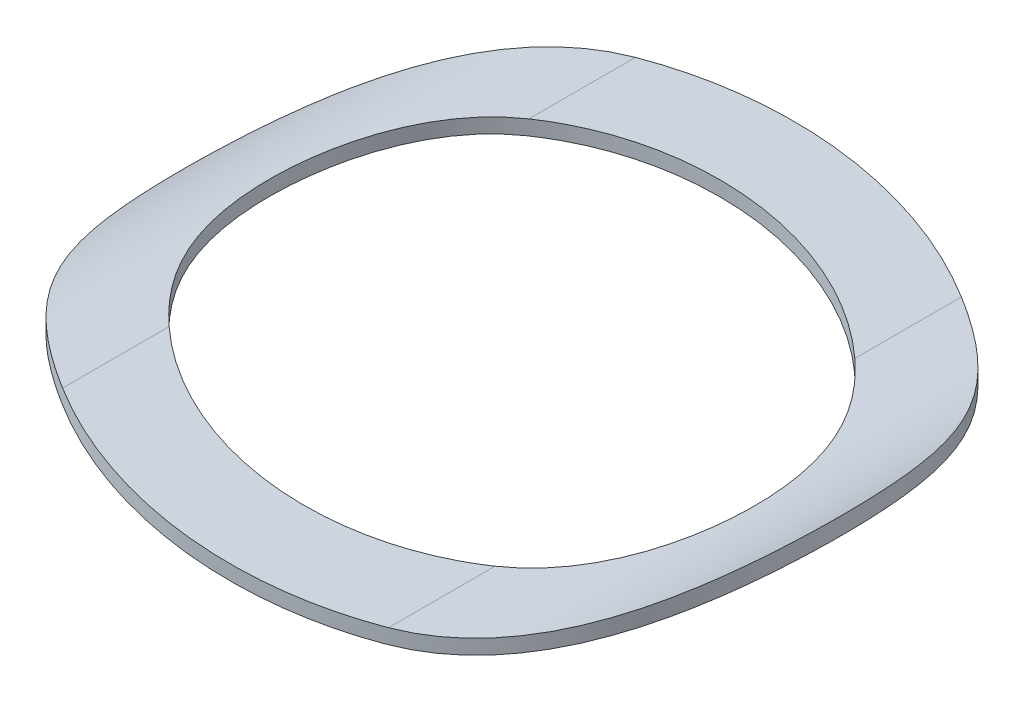
SolidWorks part; units mm, degrees
ref_plane "Front Plane" through (0, 0, 0) normal (0, 0, 1) x (1, 0, 0)
ref_plane "Top Plane" through (0, 0, 0) normal (0, 1, 0) x (1, 0, 0)
ref_plane "Right Plane" through (0, 0, 0) normal (1, 0, 0) x (0, 0, -1)
sketch "Sketch1" plane through (0, 0, 0) normal (0, 0, 1) x (1, 0, 0)
  line L0 (0, 0) -> (54.6131, 0) construction
  line L1 (-21.1111, -2) -> (56.808, -2) construction
  line L2 (6.6465, -1.908) -> (-6.6465, -0.092)
  arc A0 (-6.6465, -0.092) -> (-14, -2) centre (-8, -10) ccw
  arc A1 (6.6465, -1.908) -> (14, 0) centre (8, 8) ccw
  dimension "D4" = 20
  dimension "D1" = 2
  dimension "D2" = 8
  dimension "D3" = 8
extrude "Extrude-Thin1" add sketch "Sketch1" along normal mid plane 30 thin thin type one direction wall 0.6
sketch "Sketch2" plane through (0, 0, 0) normal (0, 1, 0) x (1, 0, 0)
  circle A0 centre (0, 0) radius 13.44
  circle A1 centre (0, 0) radius 9.9
  dimension "D1" = 26.88
  dimension "D2" = 19.8
extrude "Extrude1" cut sketch "Sketch2" against normal blind 30 flip side to cut
equation "\"D3@Sketch1\" = \"D2@Sketch1\""
